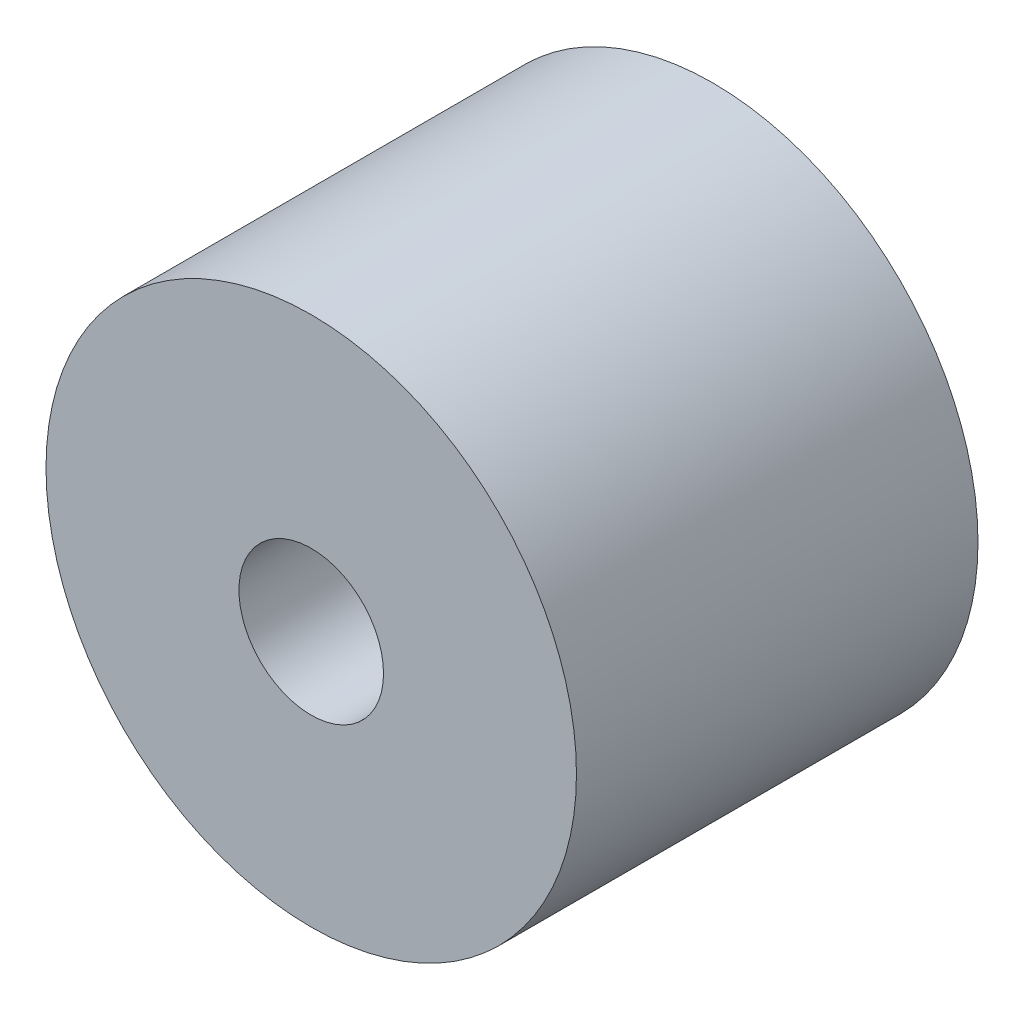
SolidWorks part; units mm, degrees
ref_plane "Front Plane" through (0, 0, 0) normal (0, 0, 1) x (1, 0, 0)
ref_plane "Top Plane" through (0, 0, 0) normal (0, 1, 0) x (1, 0, 0)
ref_plane "Right Plane" through (0, 0, 0) normal (1, 0, 0) x (0, 0, -1)
sketch "Sketch1" plane through (0, 0, 0) normal (0, 0, 1) x (1, 0, 0)
  circle A0 centre (0, -2.3727) radius 34.3491
extrude "Boss-Extrude1" add sketch "Sketch1" along normal blind 52
sketch "Sketch2" plane through (0, 0, 52) normal (0, 0, 1) x (1, 0, 0)
  circle A0 centre (0, -3.5885) radius 9.3609
extrude "Cut-Extrude1" cut sketch "Sketch2" against normal blind 52
